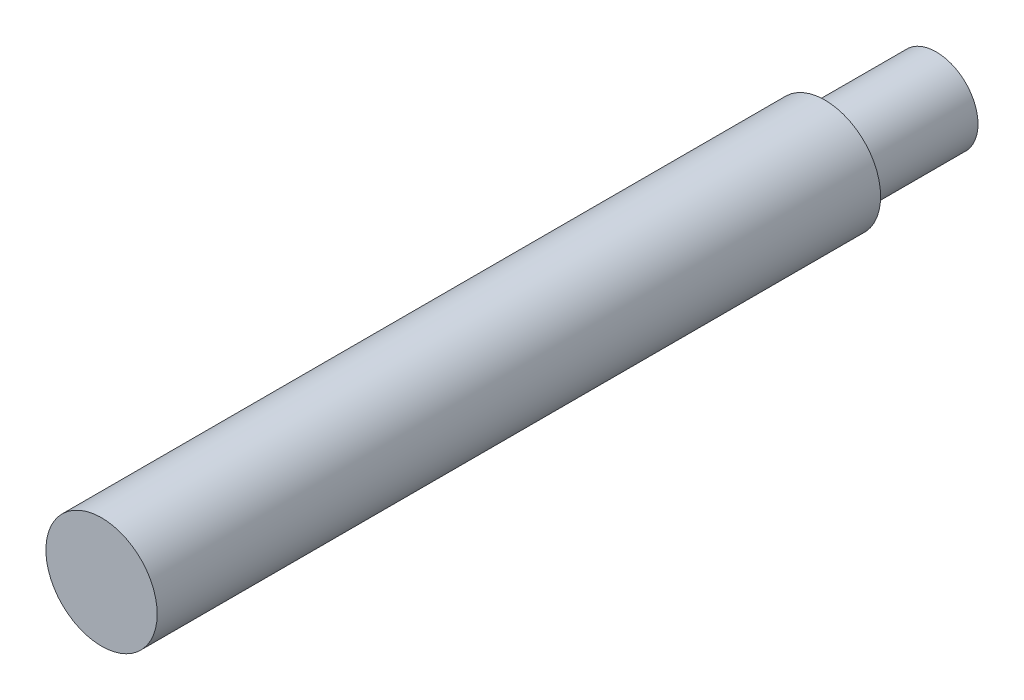
SolidWorks part; units mm, degrees
material "PW50:18:C1:0:1:2:Re:26:"
ref_plane "front" through (0, 0, 0) normal (0, 0, 1) x (1, 0, 0)
ref_plane "top" through (0, 0, 0) normal (0, 1, 0) x (1, 0, 0)
ref_plane "side" through (0, 0, 0) normal (1, 0, 0) x (0, 0, -1)
sketch "Sketch1" plane through (0, 0, 0) normal (0, 0, 1) x (1, 0, 0)
  circle A0 centre (0, 0) radius 12.7
  dimension "D1" = 25.4
extrude "Base-Extrude" add sketch "Sketch1" along normal blind 165.1
sketch "Sketch2" plane through (0, 0, 0) normal (0, 0, -1) x (-1, 0, 0)
  circle A0 centre (0, 0) radius 9.525
  dimension "D1" = 19.05
extrude "Boss-Extrude1" add sketch "Sketch2" along normal blind 25.4
